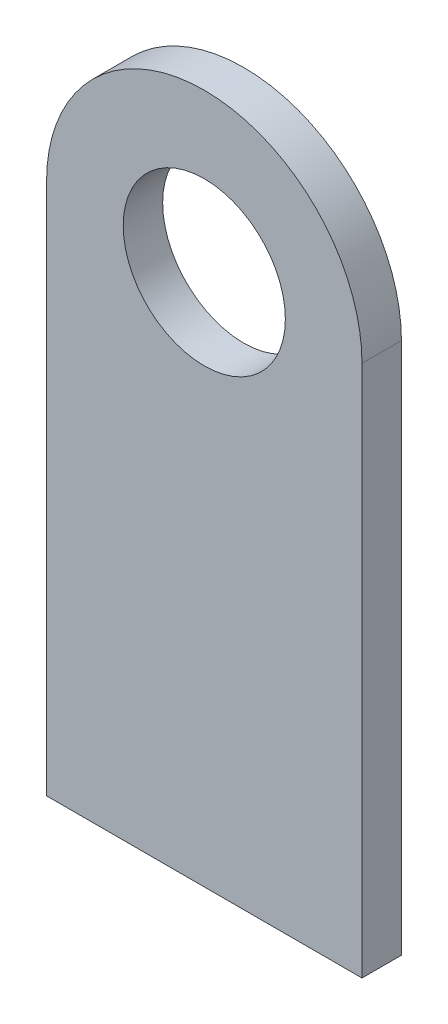
SolidWorks part; units mm, degrees
ref_plane "Front Plane" through (0, 0, 0) normal (0, 0, 1) x (1, 0, 0)
ref_plane "Top Plane" through (0, 0, 0) normal (0, 1, 0) x (1, 0, 0)
ref_plane "Right Plane" through (0, 0, 0) normal (1, 0, 0) x (0, 0, -1)
sketch "Sketch1" plane through (0, 0, 0) normal (0, 0, 1) x (1, 0, 0)
  line L0 (-6.35, -21.4313) -> (6.35, -21.4313)
  line L1 (3.2079, 5.5563) -> (-3.2079, 5.5563) construction
  line L2 (-3.2079, 5.5563) -> (-6.4158, 0) construction
  line L3 (-6.4158, 0) -> (-3.2079, -5.5562) construction
  line L4 (-3.2079, -5.5562) -> (3.2079, -5.5562) construction
  line L5 (3.2079, -5.5562) -> (6.4158, 0) construction
  line L6 (6.4158, 0) -> (3.2079, 5.5563) construction
  line L7 (6.35, -21.4313) -> (6.35, 0)
  line L8 (-6.35, 0) -> (-6.35, -21.4313)
  circle A0 centre (0, 0) radius 3.2639
  circle A1 centre (0, 0) radius 5.5563 construction
  arc A2 (6.35, 0) -> (-6.35, 0) centre (0, 0) ccw
  point P15 (5.1024, 0)
  point P16 (10.531, -22.1481)
  point P17 (9.0231, 0)
  point P18 (6.9723, 0)
  dimension "D1" = 6.5278
  dimension "D2" = 11.1125
  dimension "D3" = 15.875
  dimension "D4" = 12.7
extrude "Boss-Extrude1" add sketch "Sketch1" along normal blind 1.5875
